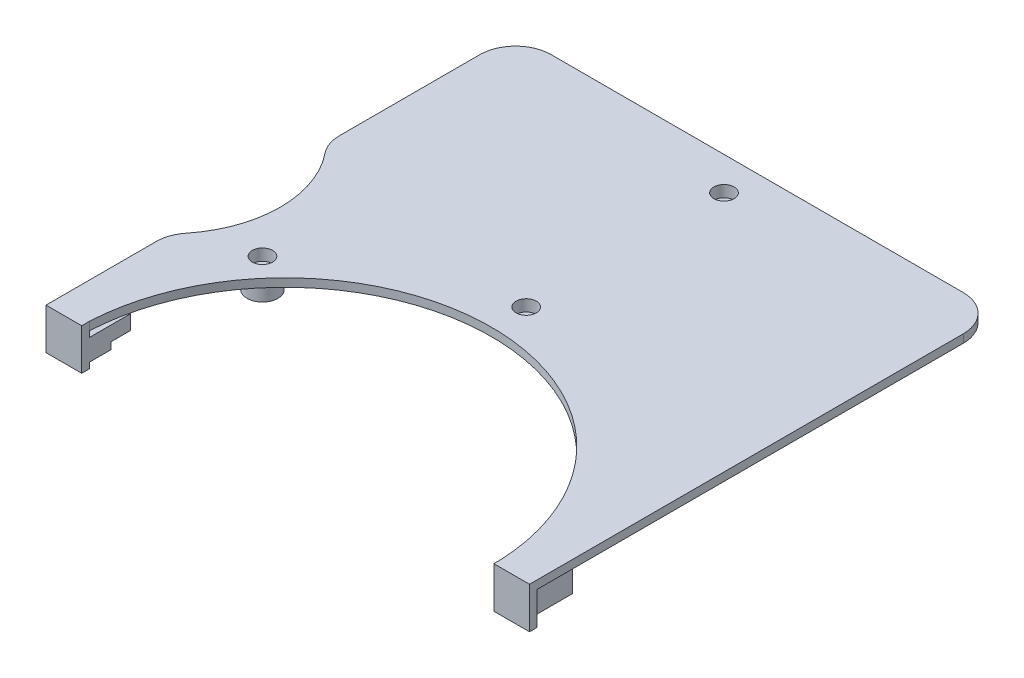
SolidWorks part; units mm, degrees
ref_plane "Front" through (0, 0, 0) normal (0, 0, 1) x (1, 0, 0)
ref_plane "Top" through (0, 0, 0) normal (0, 1, 0) x (1, 0, 0)
ref_plane "Right" through (0, 0, 0) normal (1, 0, 0) x (0, 0, -1)
sketch "Sketch1" plane through (0, 0, 0) normal (0, 1, 0) x (1, 0, 0)
  line L0 (78.0765, -38) -> (91.0765, -38)
  line L5 (-84.9235, 72.6623) -> (-84.9235, 130.1044)
  line L6 (-84.9235, 72.6623) -> (-84.9235, 61.1044)
  line L7 (91.0765, -38) -> (91.0765, 130.1044)
  line L9 (-71.9235, -38) -> (-84.9235, -38)
  line L10 (-84.9235, -38) -> (-84.9235, 0)
  line L11 (-84.9235, 4.2446) -> (-84.9235, 0)
  line L13 (-84.9235, 130.1044) -> (91.0765, 130.1044)
  arc A0 (-71.9235, -38) -> (78.0765, -38) centre (3.0765, -41.7695) cw
  arc A4 (-84.9235, 4.2446) -> (-84.9235, 61.1044) centre (-113.3535, 32.6745) ccw
  dimension "D3" = 13
  dimension "D1" = 176
  dimension "D2" = 13
extrude "Boss-Extrude1" add sketch "Sketch1" along normal blind 3
sketch "Sketch2" plane through (0, 0, 38) normal (0, 0, 1) x (1, 0, 0)
  line L1 (78.0765, 3) -> (91.0765, 3)
  line L2 (78.0765, 3) -> (78.0765, -12)
  line L3 (78.0765, -12) -> (91.0765, -12)
  line L4 (91.0765, 3) -> (91.0765, -12)
  line L5 (-84.9235, 3) -> (-71.9235, 3)
  line L6 (-84.9235, 3) -> (-84.9235, -12)
  line L7 (-84.9235, -12) -> (-71.9235, -12)
  line L8 (-71.9235, 3) -> (-71.9235, -12)
extrude "Boss-Extrude2" add sketch "Sketch2" along normal blind 2.8
sketch "Sketch3" plane through (0, 0, 38) normal (0, 0, -1) x (-1, 0, 0)
  line L0 (-78.0765, -12) -> (-91.0765, -12) construction
  line L3 (-88.9765, -9.9) -> (-78.0765, -9.9)
  line L5 (-88.9765, -2.1) -> (-78.0765, -2.1)
  line L6 (-78.0765, -9.9) -> (-78.0765, -2.1)
  line L7 (-78.0765, 0) -> (-78.0765, -12) construction
  line L8 (-78.0765, 0) -> (-91.0765, 0) construction
  line L9 (71.9235, -12) -> (71.9235, 0) construction
  line L10 (71.9235, -7.4) -> (82.8235, -7.4)
  line L11 (71.9235, -7.4) -> (71.9235, -2.1)
  line L12 (71.9235, -2.1) -> (82.8235, -2.1)
  line L15 (84.9235, -12) -> (71.9235, -12) construction
  line L16 (84.9235, 0) -> (71.9235, 0) construction
  line L19 (-88.9765, -2.1) -> (-88.9765, -9.9)
  line L20 (82.8235, -2.1) -> (82.8235, -7.4)
  dimension "D1" = 2.1
  dimension "D2" = 2.1
  dimension "D3" = 4.6
  dimension "D4" = 2.1
extrude "Boss-Extrude3" add sketch "Sketch3" along normal blind 15
sketch "Sketch4" plane through (0, 0, 38) normal (0, 0, -1) x (-1, 0, 0)
  line L0 (71.9235, -12) -> (71.9235, -7.4) construction
  line L1 (82.8235, -7.4) -> (71.9235, -7.4)
  line L2 (82.8235, -7.4) -> (82.8235, -9.9)
  line L3 (82.8235, -9.9) -> (71.9235, -9.9)
  line L4 (71.9235, -7.4) -> (71.9235, -9.9)
  line L5 (84.9235, -12) -> (71.9235, -12) construction
  dimension "D1" = 2.1
extrude "Boss-Extrude4" add sketch "Sketch4" along normal blind 7.9
fillet "Fillet3" radius 13 4 edges at (91.0765, 1.5, -130.1044) (-84.9235, 1.5, -130.1044) (-84.9235, 1.5, -61.1044) (-84.9235, 1.5, -4.2446)
sketch "Sketch5" plane through (0, 0, 0) normal (0, -1, 0) x (1, 0, 0)
  circle A2 centre (3.0765, -45.9951) radius 2.1
  circle A4 centre (3.0765, -45.9951) radius 5.6
  circle A5 centre (-60.9235, -13.9951) radius 2.1
  circle A6 centre (-60.9235, -13.9951) radius 5.6
  circle A7 centre (3.0765, -117.9951) radius 2.1
  circle A8 centre (3.0765, -117.9951) radius 5.6
extrude "Boss-Extrude5" add sketch "Sketch5" along normal blind 5
sketch "Sketch6" plane through (0, 0, 0) normal (0, -1, 0) x (-1, 0, 0)
  circle A0 centre (-3.0765, 45.9951) radius 2.1
  circle A1 centre (60.9235, 13.9951) radius 2.1
  circle A2 centre (-3.0765, 117.9951) radius 2.1
extrude "Cut-Extrude1" cut sketch "Sketch6" against normal blind 7.9
sketch "Sketch7" plane through (0, 3, 0) normal (0, 1, 0) x (1, 0, 0)
  circle A0 centre (3.0765, 45.9951) radius 3.7
  circle A1 centre (-60.9235, 13.9951) radius 3.7
  circle A2 centre (3.0765, 117.9951) radius 3.7
extrude "Cut-Extrude2" cut sketch "Sketch7" against normal blind 4.2
fillet "Fillet5" radius 2 3 edges at (3.0765, 0, -40.3951) (-60.9235, 0, -8.3951) (3.0765, 0, -112.3951)
sketch "Sketch8" plane through (0, -5, 0) normal (0, -1, 0) x (1, 0, 0)
  circle A0 centre (-60.9235, -13.9951) radius 2.1
  circle A1 centre (-60.9235, -13.9951) radius 5.6
  circle A2 centre (3.0765, -117.9951) radius 2.1
  circle A3 centre (3.0765, -117.9951) radius 5.6
extrude "Boss-Extrude6" add sketch "Sketch8" along normal blind 2.5
